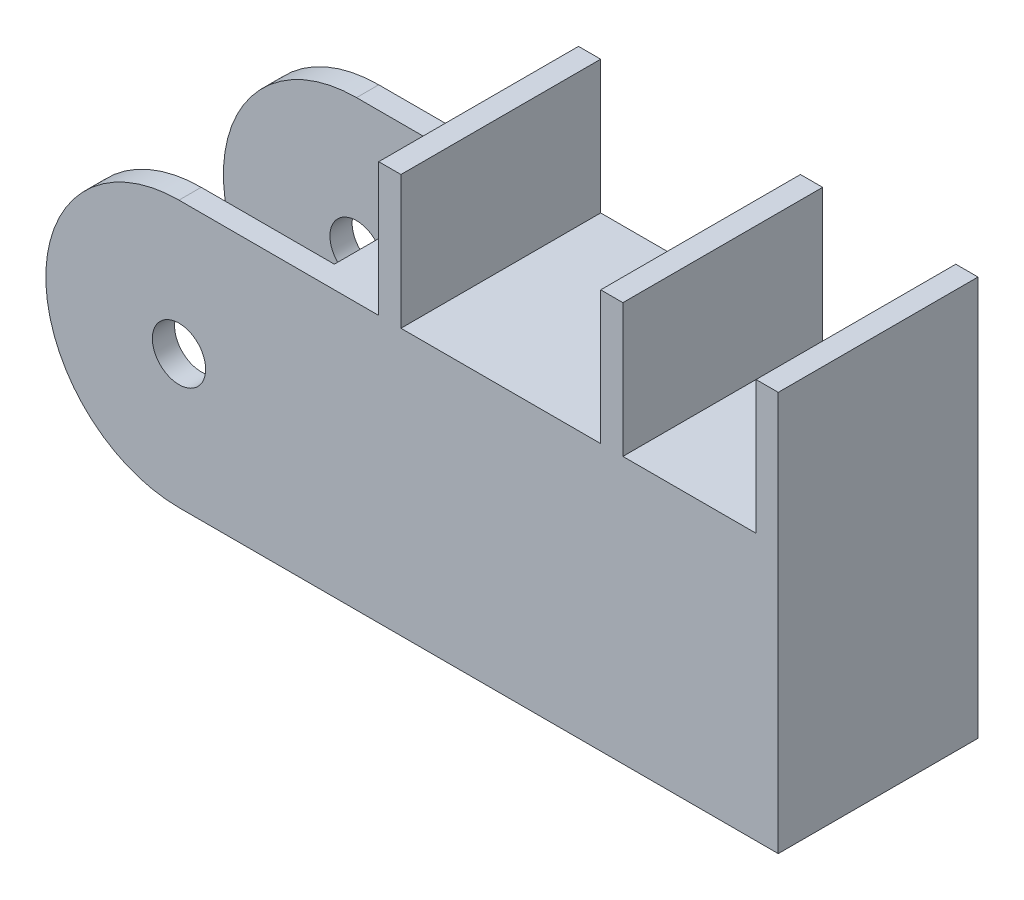
SolidWorks part; units mm, degrees
ref_plane "Płaszczyzna przednia" through (0, 0, 0) normal (0, 0, 1) x (1, 0, 0)
ref_plane "Płaszczyzna górna" through (0, 0, 0) normal (0, 1, 0) x (1, 0, 0)
ref_plane "Płaszczyzna prawa" through (0, 0, 0) normal (1, 0, 0) x (0, 0, -1)
sketch "Szkic1" plane through (0, 0, 0) normal (0, 0, 1) x (1, 0, 0)
  line L1 (-65, -30) -> (65, -30)
  line L3 (-65, 30) -> (65, 30)
  line L4 (65, -30) -> (65, 30)
  line L5 (-65, -30) -> (65, 30) construction
  line L6 (-65, 30) -> (65, -30) construction
  arc A0 (-65, -30) -> (-65, 30) centre (-65, 0) cw
  point P0 (0, 0)
  dimension "D1" = 60
  dimension "D2" = 130
extrude "Dodanie-wyciągnięcie1" add sketch "Szkic1" along normal blind 5
ref_plane "Płaszczyzna1" through (0, 0, 22.5) normal (0, 0, 1) x (1, 0, 0)
mirror "Lustro2" about plane through (0, 0, 22.5) normal (0, 0, 1) of bodies 101
sketch "Szkic2" plane through (0, 30, 0) normal (0, 1, 0) x (1, 0, 0)
  line L0 (65, -5) -> (-65, -5) construction
  line L1 (65, -40) -> (-35, -40)
  line L2 (65, -40) -> (65, -5)
  line L3 (65, -5) -> (-35, -5)
  line L4 (-35, -40) -> (-35, -5)
  dimension "D1" = 100
extrude "Dodanie-wyciągnięcie2" add sketch "Szkic2" against normal blind 5 contours L3 L4 L1 L2
mirror "Lustro3" about plane through (0, 0, 0) normal (0, 1, 0) of "Dodanie-wyciągnięcie2"
sketch "Szkic3" plane through (0, 0, 45) normal (0, 0, 1) x (1, 0, 0)
  circle A0 centre (-65, 0) radius 6
  arc A1 (-65, 30) -> (-65, -30) centre (-65, 0) ccw construction
  dimension "D1" = 12
extrude "Wytnij-wyciągnięcie1" cut sketch "Szkic3" against normal through all contours A0
sketch "Szkic4" plane through (0, 0, 45) normal (0, 0, 1) x (1, 0, 0)
  line L0 (65, 30) -> (-65, 30) construction
  line L1 (35, 30) -> (30, 30)
  line L2 (35, 30) -> (35, 60)
  line L3 (35, 60) -> (30, 60)
  line L4 (30, 30) -> (30, 60)
  line L6 (65, -30) -> (70, -30)
  line L7 (65, -30) -> (65, 60)
  line L8 (65, 60) -> (70, 60)
  line L9 (70, -30) -> (70, 60)
  line L10 (-15, 30) -> (-20, 30)
  line L11 (-15, 30) -> (-15, 60)
  line L12 (-15, 60) -> (-20, 60)
  line L13 (-20, 30) -> (-20, 60)
  dimension "D1" = 30
  dimension "D2" = 5
  dimension "D3" = 5
  dimension "D4" = 30
  dimension "D5" = 5
  dimension "D6" = 50
extrude "Dodanie-wyciągnięcie3" add sketch "Szkic4" against normal up to surface (45 mm away) up to face at (-59, 0, 0)
